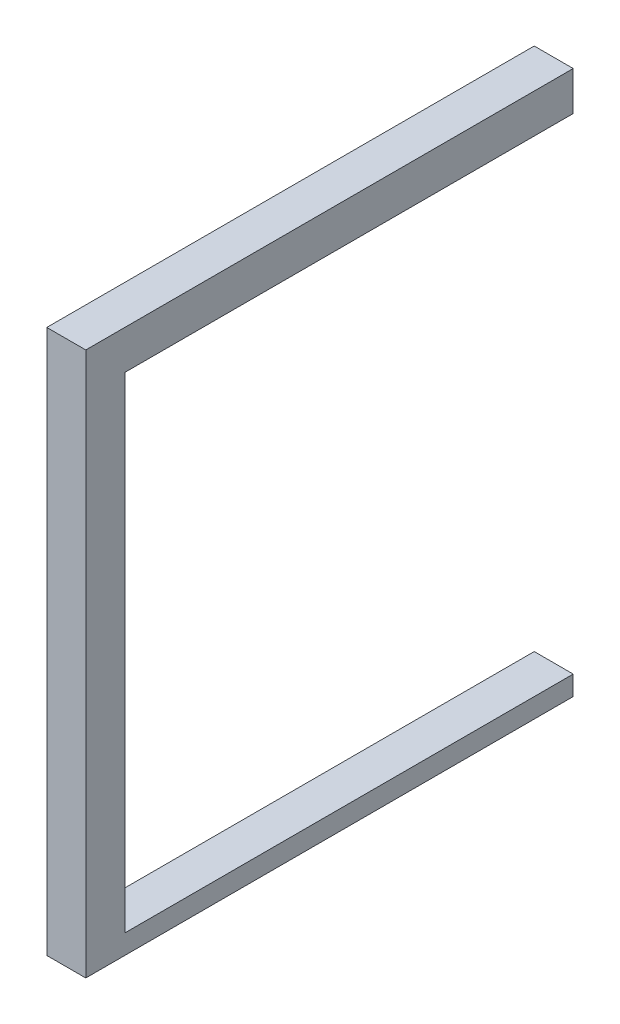
SolidWorks part; units mm, degrees
ref_plane "Front Plane" through (0, 0, 0) normal (0, 0, 1) x (1, 0, 0)
ref_plane "Top Plane" through (0, 0, 0) normal (0, 1, 0) x (1, 0, 0)
ref_plane "Right Plane" through (0, 0, 0) normal (1, 0, 0) x (0, 0, -1)
sketch "Sketch1" plane through (0, 0, 0) normal (1, 0, 0) x (0, 0, -1)
  line L0 (0, 0) -> (0, 557.9364)
  line L1 (0, 557.9364) -> (500, 557.9364)
  line L2 (500, 557.9364) -> (500, 517.9364)
  line L3 (500, 517.9364) -> (40, 517.9364)
  line L4 (40, 517.9364) -> (40, 20)
  line L5 (40, 20) -> (500, 20)
  line L6 (500, 20) -> (500, 0)
  line L7 (500, 0) -> (0, 0)
  dimension "D1" = 500
  dimension "D2" = 20
  dimension "D3" = 40
  dimension "D4" = 40
extrude "Boss-Extrude1" add sketch "Sketch1" along normal blind 40
